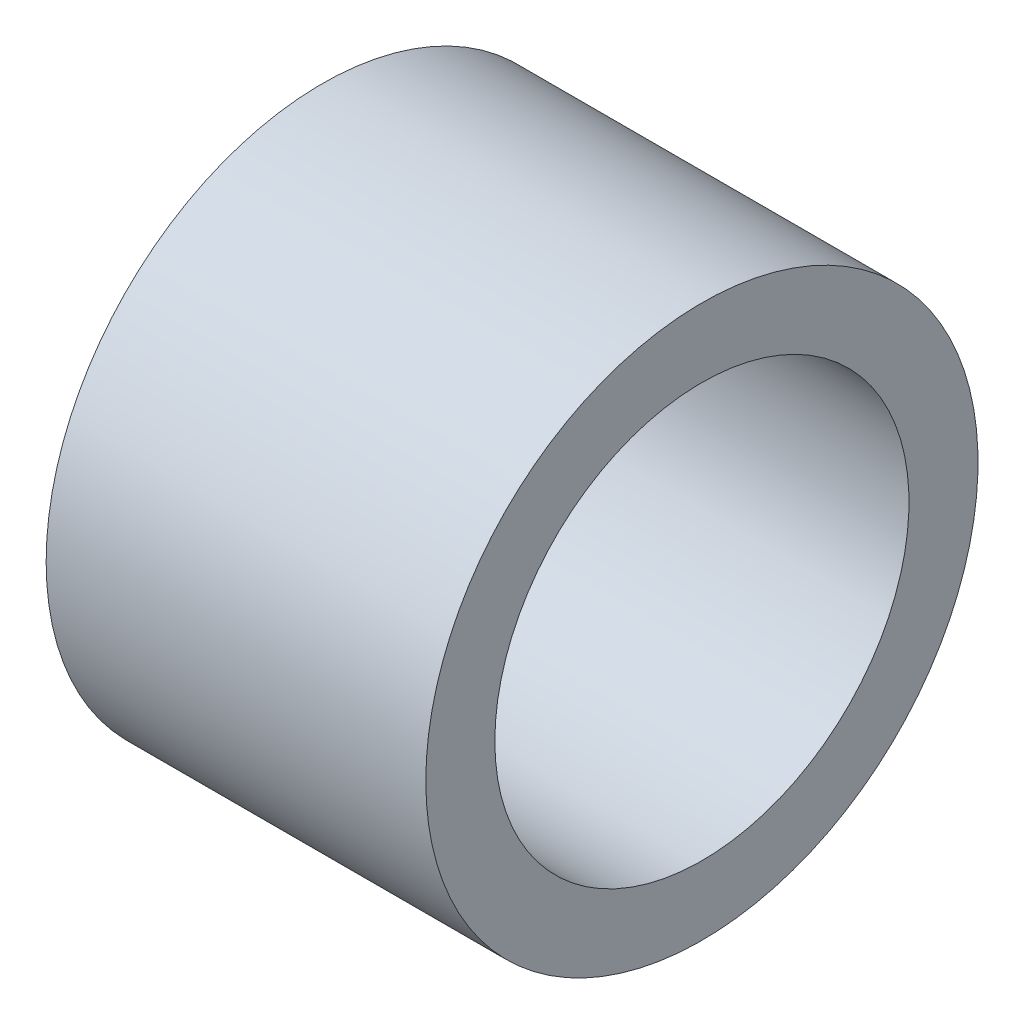
SolidWorks part; units mm, degrees
material "MCナイロン"
ref_plane "Front Plane" through (0, 0, 0) normal (0, 0, 1) x (1, 0, 0)
ref_plane "Top Plane" through (0, 0, 0) normal (0, 1, 0) x (1, 0, 0)
ref_plane "Right Plane" through (0, 0, 0) normal (1, 0, 0) x (0, 0, -1)
sketch "Sketch1" plane through (0, 0, 0) normal (0, 0, 1) x (1, 0, 0)
  line L0 (0, 0) -> (5.5, 0) construction
  line L1 (0, 3) -> (5.5, 3)
  line L2 (0, -3) -> (5.5, -3) construction
  line L3 (0, 3) -> (0, 4)
  line L4 (0, 4) -> (5.5, 4)
  line L5 (5.5, 3) -> (5.5, 4)
  dimension "D" = 8
  dimension "V" = 6
  dimension "T" = 5.5
revolve "Revolve1" add sketch "Sketch1" angle 360 about L0
